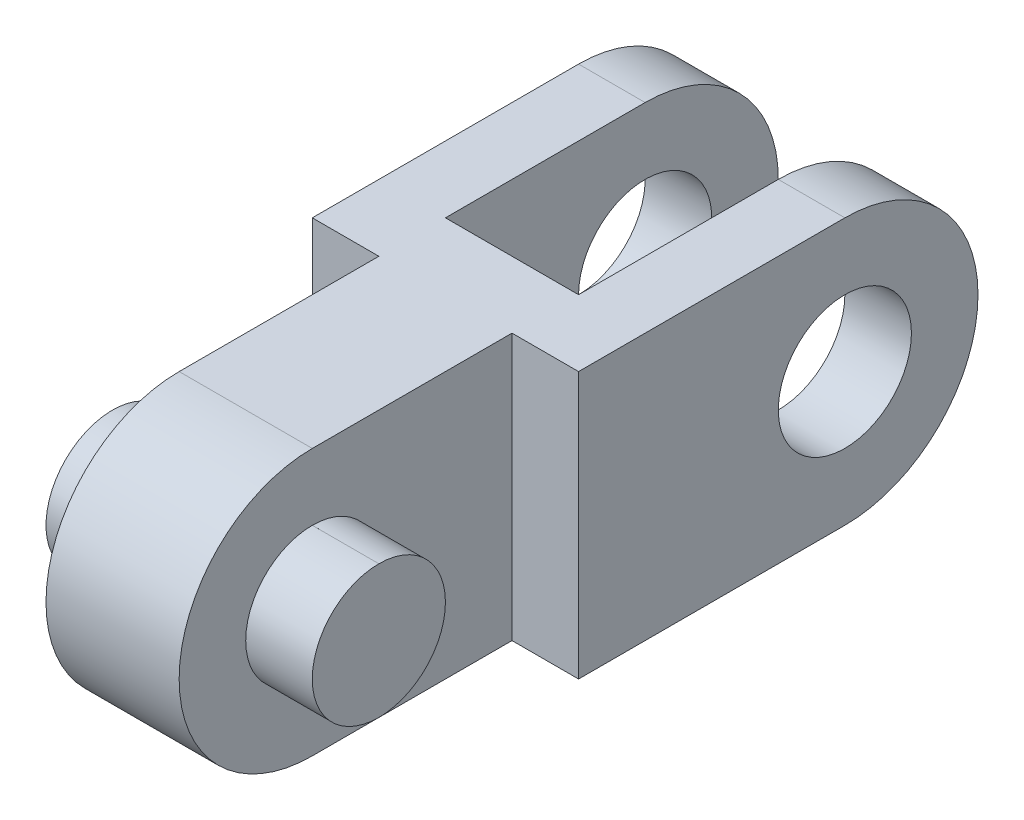
SolidWorks part; units mm, degrees
ref_plane "Front Plane" through (0, 0, 0) normal (0, 0, 1) x (1, 0, 0)
ref_plane "Top Plane" through (0, 0, 0) normal (0, 1, 0) x (1, 0, 0)
ref_plane "Right Plane" through (0, 0, 0) normal (1, 0, 0) x (0, 0, -1)
ref_plane "Plane1" through (0, 0, 0) normal (-1, 0, 0) x (0, -1, 0)
sketch "Sketch1" plane through (0, 0, 0) normal (-1, 0, 0) x (0, -1, 0)
  line L0 (0, 22.5) -> (0, 5)
  line L1 (10, 5) -> (10, 22.5)
  arc A0 (0, 5) -> (10, 5) centre (5, 5) ccw
  arc A1 (10, 22.5) -> (0, 22.5) centre (5, 22.5) ccw
extrude "Boss-Extrude1" add sketch "Sketch1" against normal blind 10
sketch "Sketch2" plane through (0, 0, 0) normal (0, 1, 0) x (-1, 0, 0)
  line L0 (0, 22.5) -> (-2.5, 22.5)
  line L1 (-2.5, 22.5) -> (-2.5, 15)
  line L2 (-2.5, 15) -> (0, 15)
  line L3 (0, 15) -> (0, 22.5)
extrude "Cut-Extrude1" cut sketch "Sketch2" against normal through all
sketch "Sketch3" plane through (0, 0, 0) normal (0, 1, 0) x (-1, 0, 0)
  line L0 (-7.5, 5) -> (-2.5, 5)
  line L1 (-2.5, 5) -> (-2.5, 12.5)
  line L2 (-2.5, 12.5) -> (-7.5, 12.5)
  line L3 (-7.5, 12.5) -> (-7.5, 5)
extrude "Cut-Extrude2" cut sketch "Sketch3" against normal through all
sketch "Sketch4" plane through (0, 0, 0) normal (0, 1, 0) x (-1, 0, 0)
  line L0 (-10, 22.5) -> (-10, 15)
  line L1 (-10, 15) -> (-7.5, 15)
  line L2 (-7.5, 15) -> (-7.5, 22.5)
  line L3 (-7.5, 22.5) -> (-10, 22.5)
extrude "Cut-Extrude3" cut sketch "Sketch4" against normal through all
ref_plane "Plane2" through (0, 0, 22.5) normal (0, 0, 1) x (1, 0, 0)
sketch "Sketch5" plane through (0, 0, 22.5) normal (0, 0, 1) x (1, 0, 0)
  line L0 (7.5, -2.5) -> (7.5, -5)
  line L1 (7.5, -5) -> (10, -5)
  line L2 (10, -5) -> (10, -2.5)
  line L3 (10, -2.5) -> (7.5, -2.5)
  line L4 (7.5, -5) -> (10, -5) construction
revolve "Revolve1" add sketch "Sketch5" angle 360 about L4
sketch "Sketch6" plane through (0, 0, 22.5) normal (0, 0, 1) x (1, 0, 0)
  line L0 (0, -2.5) -> (0, -5)
  line L1 (0, -5) -> (2.5, -5)
  line L2 (2.5, -5) -> (2.5, -2.5)
  line L3 (2.5, -2.5) -> (0, -2.5)
  line L4 (0, -5) -> (2.5, -5) construction
revolve "Revolve2" add sketch "Sketch6" angle 360 about L4
hole_wizard "Ø5.0 (5) Diameter Hole1" positions "Sketch8" profile "Sketch7" hole size "Ø5.0" standard "ANSI Metric"
sketch "Sketch8" plane through (0, 0, 0) normal (-1, 0, 0) x (0, 0, 1)
  point P0 (5, -5)
sketch "Sketch7" plane through (0, -5, 5) normal (0, 1, 0) x (0, 0, 1)
  line L0 (0, 0) -> (0, 2.5)
  line L1 (0, 2.5) -> (2.5, 2.5)
  line L2 (2.5, 2.5) -> (2.5, 0)
  line L5 (2.5, 0) -> (0, 0)
  line L11 (0, -6.35) -> (0, 107.95) construction
  dimension "Thru Hole Dia." = 5
  dimension "Thru Hole Depth" = 2.5
hole_wizard "Ø5.0 (5) Diameter Hole2" positions "Sketch10" profile "Sketch9" hole size "Ø5.0" standard "ANSI Metric"
sketch "Sketch10" plane through (10, 0, 0) normal (1, 0, 0) x (0, 0, -1)
  point P0 (-5, -5)
sketch "Sketch9" plane through (10, -5, 5) normal (0, 1, 0) x (0, 0, -1)
  line L0 (0, 0) -> (0, 2.5)
  line L1 (0, 2.5) -> (2.5, 2.5)
  line L2 (2.5, 2.5) -> (2.5, 0)
  line L5 (2.5, 0) -> (0, 0)
  line L11 (0, -6.35) -> (0, 107.95) construction
  dimension "Thru Hole Dia." = 5
  dimension "Thru Hole Depth" = 2.5
sketch "Sketch11" plane through (0, -10, 0) normal (0, -1, 0) x (1, 0, 0)
  line L1 (2.5, 5) -> (7.5, 5)
  line L2 (2.5, 5) -> (2.5, -0.8163)
  line L3 (2.5, -0.8163) -> (7.5, -0.8163)
  line L4 (7.5, 5) -> (7.5, -0.8163)
  dimension "D1" = 5
extrude "Cut-Extrude4" cut sketch "Sketch11" against normal blind 10
sketch "Sketch12" plane through (10, 0, 0) normal (1, 0, 0) x (0, 0, -1)
  line L0 (-22.5, -10) -> (-22.5, -7.5) construction
  line L1 (-22.5, 5.4719) -> (-22.5, -5.4719) construction
  line L2 (-15, -10) -> (-22.5, -10) construction
  line L5 (-22.5, -7.5) -> (-22.5, -10.0001)
  line L6 (-22.5, 0) -> (-22.5, -2.5001)
  arc A0 (-22.5, -7.5) -> (-22.5, -2.5) centre (-22.5, -5) ccw construction
  arc A1 (-22.5, -7.5) -> (-22.5, -2.5001) centre (-22.5, -5) cw
  arc A2 (-22.5, 0) -> (-22.5, -10.0001) centre (-22.5, -5) ccw
extrude "Cut-Extrude5" cut sketch "Sketch12" against normal blind 2.5
ref_plane "Plane4" through (5, 0, 0) normal (1, 0, 0) x (0, 0, -1)
sketch "Sketch13" plane through (0, 0, 0) normal (-1, 0, 0) x (0, 0, 1)
  line L0 (22.5, 0) -> (22.5, -5) construction
  line L4 (22.5, 0) -> (22.5, -2.5)
  line L5 (22.5, -7.5) -> (22.5, -10)
  arc A3 (22.5, 0) -> (22.5, -10) centre (22.5, -5) cw
  arc A4 (22.5, -10) -> (22.5, 0) centre (22.5, -5) ccw construction
  arc A5 (22.5, -2.5) -> (22.5, -7.5) centre (22.5, -5) cw
  arc A6 (22.5, -2.5) -> (22.5, -7.5) centre (22.5, -5) ccw construction
extrude "Cut-Extrude6" cut sketch "Sketch13" against normal blind 2.5
